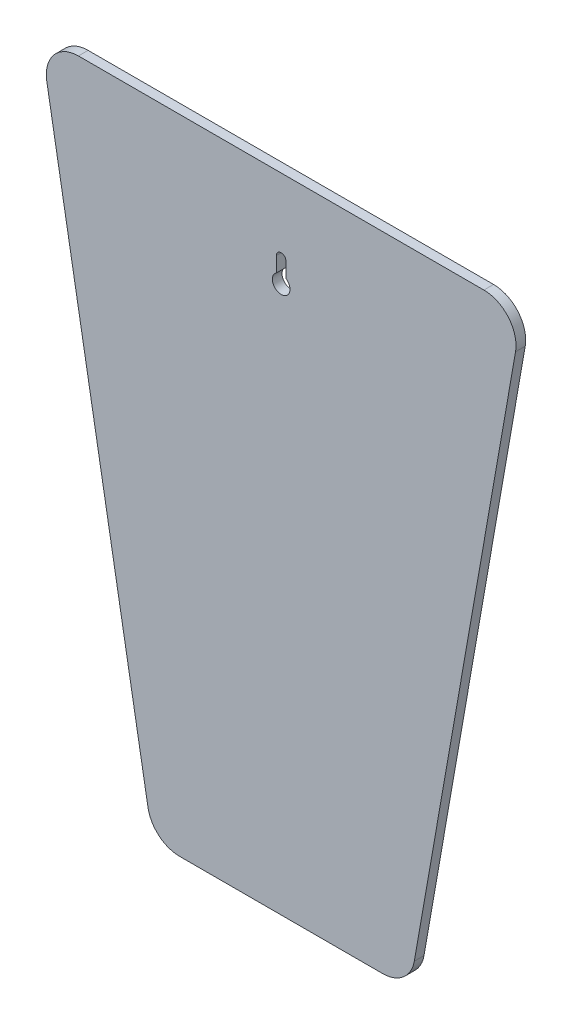
SolidWorks part; units mm, degrees
ref_plane "Front Plane" through (0, 0, 0) normal (0, 0, 1) x (1, 0, 0)
ref_plane "Top Plane" through (0, 0, 0) normal (0, 1, 0) x (1, 0, 0)
ref_plane "Right Plane" through (0, 0, 0) normal (1, 0, 0) x (0, 0, -1)
sketch "Sketch1" plane through (0, 0, 0) normal (0, 0, 1) x (1, 0, 0)
  line L0 (-40, 0) -> (40, 0)
  line L1 (0, 0) -> (0, 200) construction
  line L2 (-75, 200) -> (75, 200)
  line L3 (-75, 200) -> (-40, 0)
  line L4 (75, 200) -> (40, 0)
  point P4 (0, 0)
  point P10 (0, 200)
  dimension "D1" = 80
  dimension "D2" = 200
  dimension "D3" = 150
extrude "Boss-Extrude1" add sketch "Sketch1" along normal blind 3 and the other way blind 0.01
fillet "Fillet1" radius 10 1 edges at (75, 200, 1.495)
fillet "Fillet2" radius 10 1 edges at (40, 0, 1.495)
fillet "Fillet3" radius 10 1 edges at (-40, 0, 1.495)
fillet "Fillet4" radius 10 1 edges at (-75, 200, 1.495)
sketch "Sketch4" plane through (0, 0, 3) normal (0, 0, 1) x (1, 0, 0)
  line L0 (0, 200) -> (0, 118.0918) construction
  line L1 (63.098, 200) -> (-63.098, 200) construction
  line L2 (0, 170) -> (0, 177) construction
  line L3 (-1.5, 170) -> (-1.5, 177)
  line L4 (1.5, 170) -> (1.5, 177)
  circle A0 centre (0, 170) radius 2.75
  arc A1 (-1.5, 170) -> (1.5, 170) centre (0, 170) ccw
  arc A2 (1.5, 177) -> (-1.5, 177) centre (0, 177) ccw
  point P7 (0, 173.5)
  dimension "D2" = 5.5
  dimension "D1" = 30
  dimension "D3" = 3
  dimension "D4" = 7
extrude "Cut-Extrude8" cut sketch "Sketch4" against normal blind 10 contours L4 A2 L3 A0 | A1 L3 A0 L4 | L3 A1 L4 A0
